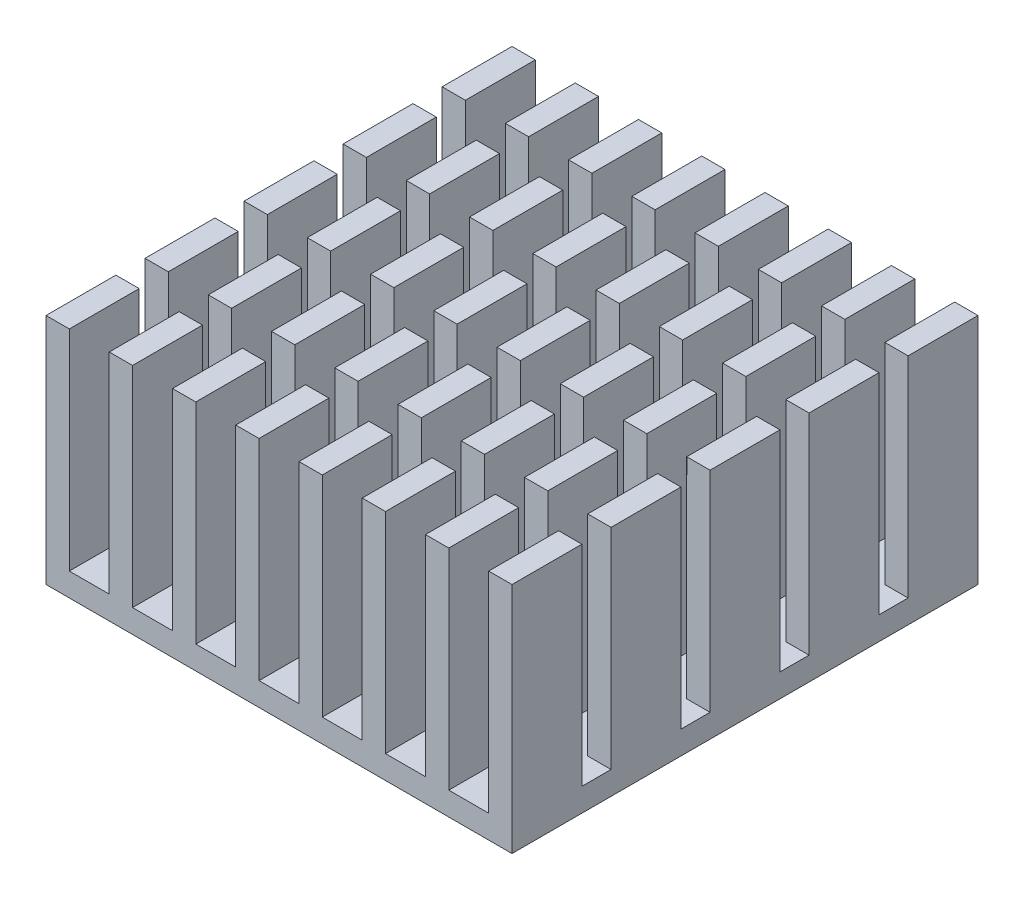
SolidWorks part; units mm, degrees
ref_plane "Front Plane" through (0, 0, 0) normal (0, 0, 1) x (1, 0, 0)
ref_plane "Top Plane" through (0, 0, 0) normal (0, 1, 0) x (1, 0, 0)
ref_plane "Right Plane" through (0, 0, 0) normal (1, 0, 0) x (0, 0, -1)
sketch "Sketch1" plane through (0, 0, 0) normal (0, 1, 0) x (1, 0, 0)
  line L1 (-10, -10) -> (10, -10)
  line L2 (-10, -10) -> (-10, 10)
  line L3 (-10, 10) -> (10, 10)
  line L4 (10, -10) -> (10, 10)
  line L5 (-10, -10) -> (10, 10) construction
  line L6 (-10, 10) -> (10, -10) construction
  point P0 (0, 0)
  dimension "D1" = 20
  dimension "D2" = 20
extrude "Boss-Extrude1" add sketch "Sketch1" along normal blind 1
sketch "Sketch2" plane through (0, 1, 0) normal (0, 1, 0) x (1, 0, 0)
  line L0 (-10, 10) -> (-10, 7)
  line L1 (-10, 10) -> (-10, -10) construction
  line L2 (-7.2857, 10) -> (-7.2857, 7)
  line L3 (-10, 10) -> (-9, 10)
  line L4 (-10, 10) -> (-10, 7)
  line L5 (-10, 7) -> (-9, 7)
  line L6 (-9, 10) -> (-9, 7)
  line L7 (-7.2857, 10) -> (-6.2857, 10)
  line L8 (-6.2857, 10) -> (-6.2857, 7)
  line L9 (-7.2857, 7) -> (-6.2857, 7)
  line L10 (-4.5714, 10) -> (-4.5714, 7)
  line L11 (-4.5714, 10) -> (-3.5714, 10)
  line L12 (-3.5714, 10) -> (-3.5714, 7)
  line L13 (-4.5714, 7) -> (-3.5714, 7)
  line L14 (-1.8571, 10) -> (-1.8571, 7)
  line L15 (-1.8571, 10) -> (-0.8571, 10)
  line L16 (-0.8571, 10) -> (-0.8571, 7)
  line L17 (-1.8571, 7) -> (-0.8571, 7)
  line L18 (0.8571, 10) -> (0.8571, 7)
  line L19 (0.8571, 10) -> (1.8571, 10)
  line L20 (1.8571, 10) -> (1.8571, 7)
  line L21 (0.8571, 7) -> (1.8571, 7)
  line L22 (3.5714, 10) -> (3.5714, 7)
  line L23 (3.5714, 10) -> (4.5714, 10)
  line L24 (4.5714, 10) -> (4.5714, 7)
  line L25 (3.5714, 7) -> (4.5714, 7)
  line L26 (6.2857, 10) -> (6.2857, 7)
  line L27 (6.2857, 10) -> (7.2857, 10)
  line L28 (7.2857, 10) -> (7.2857, 7)
  line L29 (6.2857, 7) -> (7.2857, 7)
  line L30 (9, 10) -> (9, 7)
  line L31 (9, 10) -> (10, 10)
  line L32 (10, 10) -> (10, 7)
  line L33 (9, 7) -> (10, 7)
  line L34 (-7.2857, 5.75) -> (-7.2857, 2.75)
  line L35 (-7.2857, 5.75) -> (-6.2857, 5.75)
  line L36 (-6.2857, 5.75) -> (-6.2857, 2.75)
  line L37 (-7.2857, 2.75) -> (-6.2857, 2.75)
  line L38 (-4.5714, 5.75) -> (-4.5714, 2.75)
  line L39 (-4.5714, 5.75) -> (-3.5714, 5.75)
  line L40 (-3.5714, 5.75) -> (-3.5714, 2.75)
  line L41 (-4.5714, 2.75) -> (-3.5714, 2.75)
  line L42 (-1.8571, 5.75) -> (-1.8571, 2.75)
  line L43 (-1.8571, 5.75) -> (-0.8571, 5.75)
  line L44 (-0.8571, 5.75) -> (-0.8571, 2.75)
  line L45 (-1.8571, 2.75) -> (-0.8571, 2.75)
  line L46 (0.8571, 5.75) -> (0.8571, 2.75)
  line L47 (0.8571, 5.75) -> (1.8571, 5.75)
  line L48 (1.8571, 5.75) -> (1.8571, 2.75)
  line L49 (0.8571, 2.75) -> (1.8571, 2.75)
  line L50 (3.5714, 5.75) -> (3.5714, 2.75)
  line L51 (3.5714, 5.75) -> (4.5714, 5.75)
  line L52 (4.5714, 5.75) -> (4.5714, 2.75)
  line L53 (3.5714, 2.75) -> (4.5714, 2.75)
  line L54 (6.2857, 5.75) -> (6.2857, 2.75)
  line L55 (6.2857, 5.75) -> (7.2857, 5.75)
  line L56 (7.2857, 5.75) -> (7.2857, 2.75)
  line L57 (6.2857, 2.75) -> (7.2857, 2.75)
  line L58 (9, 5.75) -> (9, 2.75)
  line L59 (9, 5.75) -> (10, 5.75)
  line L60 (10, 5.75) -> (10, 2.75)
  line L61 (9, 2.75) -> (10, 2.75)
  line L62 (-7.2857, 1.5) -> (-7.2857, -1.5)
  line L63 (-7.2857, 1.5) -> (-6.2857, 1.5)
  line L64 (-6.2857, 1.5) -> (-6.2857, -1.5)
  line L65 (-7.2857, -1.5) -> (-6.2857, -1.5)
  line L66 (-4.5714, 1.5) -> (-4.5714, -1.5)
  line L67 (-4.5714, 1.5) -> (-3.5714, 1.5)
  line L68 (-3.5714, 1.5) -> (-3.5714, -1.5)
  line L69 (-4.5714, -1.5) -> (-3.5714, -1.5)
  line L70 (-1.8571, 1.5) -> (-1.8571, -1.5)
  line L71 (-1.8571, 1.5) -> (-0.8571, 1.5)
  line L72 (-0.8571, 1.5) -> (-0.8571, -1.5)
  line L73 (-1.8571, -1.5) -> (-0.8571, -1.5)
  line L74 (0.8571, 1.5) -> (0.8571, -1.5)
  line L75 (0.8571, 1.5) -> (1.8571, 1.5)
  line L76 (1.8571, 1.5) -> (1.8571, -1.5)
  line L77 (0.8571, -1.5) -> (1.8571, -1.5)
  line L78 (3.5714, 1.5) -> (3.5714, -1.5)
  line L79 (3.5714, 1.5) -> (4.5714, 1.5)
  line L80 (4.5714, 1.5) -> (4.5714, -1.5)
  line L81 (3.5714, -1.5) -> (4.5714, -1.5)
  line L82 (6.2857, 1.5) -> (6.2857, -1.5)
  line L83 (6.2857, 1.5) -> (7.2857, 1.5)
  line L84 (7.2857, 1.5) -> (7.2857, -1.5)
  line L85 (6.2857, -1.5) -> (7.2857, -1.5)
  line L86 (9, 1.5) -> (9, -1.5)
  line L87 (9, 1.5) -> (10, 1.5)
  line L88 (10, 1.5) -> (10, -1.5)
  line L89 (9, -1.5) -> (10, -1.5)
  line L90 (-7.2857, -2.75) -> (-7.2857, -5.75)
  line L91 (-7.2857, -2.75) -> (-6.2857, -2.75)
  line L92 (-6.2857, -2.75) -> (-6.2857, -5.75)
  line L93 (-7.2857, -5.75) -> (-6.2857, -5.75)
  line L94 (-4.5714, -2.75) -> (-4.5714, -5.75)
  line L95 (-4.5714, -2.75) -> (-3.5714, -2.75)
  line L96 (-3.5714, -2.75) -> (-3.5714, -5.75)
  line L97 (-4.5714, -5.75) -> (-3.5714, -5.75)
  line L98 (-1.8571, -2.75) -> (-1.8571, -5.75)
  line L99 (-1.8571, -2.75) -> (-0.8571, -2.75)
  line L100 (-0.8571, -2.75) -> (-0.8571, -5.75)
  line L101 (-1.8571, -5.75) -> (-0.8571, -5.75)
  line L102 (0.8571, -2.75) -> (0.8571, -5.75)
  line L103 (0.8571, -2.75) -> (1.8571, -2.75)
  line L104 (1.8571, -2.75) -> (1.8571, -5.75)
  line L105 (0.8571, -5.75) -> (1.8571, -5.75)
  line L106 (3.5714, -2.75) -> (3.5714, -5.75)
  line L107 (3.5714, -2.75) -> (4.5714, -2.75)
  line L108 (4.5714, -2.75) -> (4.5714, -5.75)
  line L109 (3.5714, -5.75) -> (4.5714, -5.75)
  line L110 (6.2857, -2.75) -> (6.2857, -5.75)
  line L111 (6.2857, -2.75) -> (7.2857, -2.75)
  line L112 (7.2857, -2.75) -> (7.2857, -5.75)
  line L113 (6.2857, -5.75) -> (7.2857, -5.75)
  line L114 (9, -2.75) -> (9, -5.75)
  line L115 (9, -2.75) -> (10, -2.75)
  line L116 (10, -2.75) -> (10, -5.75)
  line L117 (9, -5.75) -> (10, -5.75)
  line L118 (-7.2857, -7) -> (-7.2857, -10)
  line L119 (-7.2857, -7) -> (-6.2857, -7)
  line L120 (-6.2857, -7) -> (-6.2857, -10)
  line L121 (-7.2857, -10) -> (-6.2857, -10)
  line L122 (-4.5714, -7) -> (-4.5714, -10)
  line L123 (-4.5714, -7) -> (-3.5714, -7)
  line L124 (-3.5714, -7) -> (-3.5714, -10)
  line L125 (-4.5714, -10) -> (-3.5714, -10)
  line L126 (-1.8571, -7) -> (-1.8571, -10)
  line L127 (-1.8571, -7) -> (-0.8571, -7)
  line L128 (-0.8571, -7) -> (-0.8571, -10)
  line L129 (-1.8571, -10) -> (-0.8571, -10)
  line L130 (0.8571, -7) -> (0.8571, -10)
  line L131 (0.8571, -7) -> (1.8571, -7)
  line L132 (1.8571, -7) -> (1.8571, -10)
  line L133 (0.8571, -10) -> (1.8571, -10)
  line L134 (3.5714, -7) -> (3.5714, -10)
  line L135 (3.5714, -7) -> (4.5714, -7)
  line L136 (4.5714, -7) -> (4.5714, -10)
  line L137 (3.5714, -10) -> (4.5714, -10)
  line L138 (6.2857, -7) -> (6.2857, -10)
  line L139 (6.2857, -7) -> (7.2857, -7)
  line L140 (7.2857, -7) -> (7.2857, -10)
  line L141 (6.2857, -10) -> (7.2857, -10)
  line L142 (9, -7) -> (9, -10)
  line L143 (9, -7) -> (10, -7)
  line L144 (10, -7) -> (10, -10)
  line L145 (9, -10) -> (10, -10)
  line L146 (-10, 5.75) -> (-10, 2.75)
  line L147 (-10, 5.75) -> (-9, 5.75)
  line L148 (-9, 5.75) -> (-9, 2.75)
  line L149 (-10, 2.75) -> (-9, 2.75)
  line L150 (-10, 1.5) -> (-10, -1.5)
  line L151 (-10, 1.5) -> (-9, 1.5)
  line L152 (-9, 1.5) -> (-9, -1.5)
  line L153 (-10, -1.5) -> (-9, -1.5)
  line L154 (-10, -2.75) -> (-10, -5.75)
  line L155 (-10, -2.75) -> (-9, -2.75)
  line L156 (-9, -2.75) -> (-9, -5.75)
  line L157 (-10, -5.75) -> (-9, -5.75)
  line L158 (-10, -7) -> (-10, -10)
  line L159 (-10, -7) -> (-9, -7)
  line L160 (-9, -7) -> (-9, -10)
  line L161 (-10, -10) -> (-9, -10)
  line M6 (10, -10) -> (10, 10)
  line M7 (10, 10) -> (-10, 10)
  line M8 (-10, 10) -> (-10, -10)
  line M9 (-10, -10) -> (10, -10)
  dimension "D1" = 1
  dimension "D2" = 3
  dimension "D3" = 8
  dimension "D4" = 5
extrude "Boss-Extrude2" add sketch "Sketch2" along normal blind 9 contours L6 L5 M7 M8 | L2 L9 L8 M7 | L10 L13 L12 M7 | L14 L17 L16 M7 | L18 L21 L20 M7 | L22 L25 L24 M7 | L26 L29 L28 M7 | L30 L33 M6 M7 | L54 L57 L56 L55 | L50 L53 L52 L51 | L46 L49 L48 L47 | L42 L45 L44 L43 | L38 L41 L40 L39 | L149 L148 L147 M8 | L62 L65 L64 L63 | L66 L69 L68 L67 | L70 L73 L72 L71 | L74 L77 L76 L75 | L82 L85 L84 L83 | L86 L89 L87 M6 | L114 L117 L115 M6 | L110 L113 L112 L111 | L106 L109 L108 L107 | L102 L105 L104 L103 | L98 L101 L100 L99 | L94 L97 L96 L95 | L90 L93 L92 L91 | L157 L156 L155 M8 | L160 L159 M8 M9 | L120 L119 L118 M9 | L124 L123 L122 M9 | L128 L127 L126 M9 | L132 L131 L130 M9 | L136 L135 L134 M9 | L140 L139 L138 M9 | L143 L142 M9 M6 | L60 L61 L58 L59 | L34 L37 L36 L35 | L152 L153 L150 L151 | L78 L81 L80 L79
